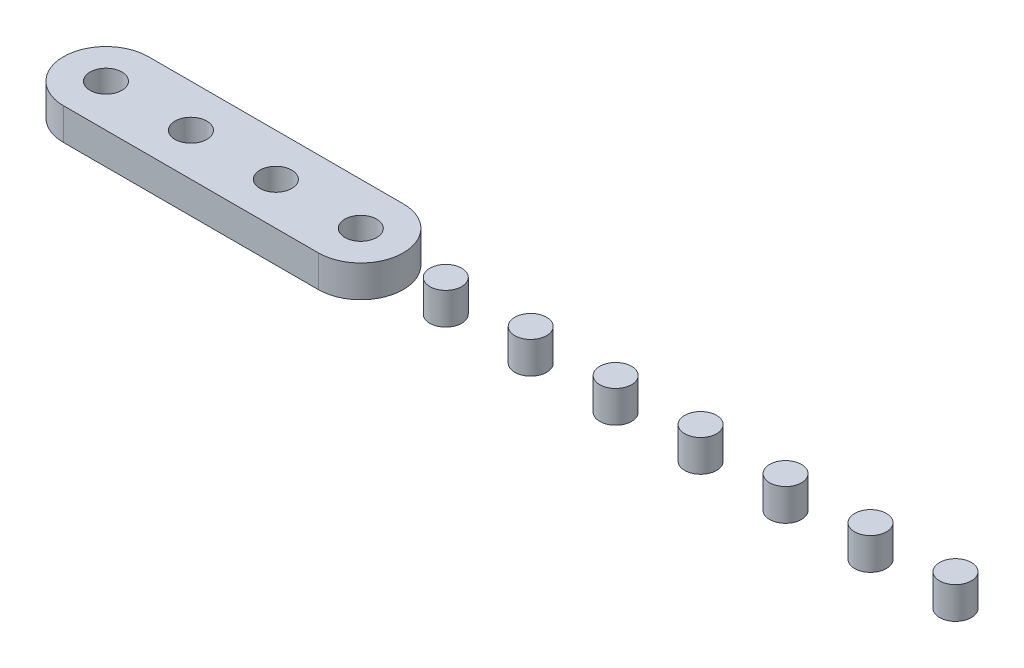
SolidWorks part; units mm, degrees
ref_plane "Front Plane" through (0, 0, 0) normal (0, 0, 1) x (1, 0, 0)
ref_plane "Top Plane" through (0, 0, 0) normal (0, 1, 0) x (1, 0, 0)
ref_plane "Right Plane" through (0, 0, 0) normal (1, 0, 0) x (0, 0, -1)
sketch "Sketch2" plane through (0, 0, 0) normal (0, 1, 0) x (1, 0, 0)
  line L0 (0, 0) -> (24, 0) construction
  line L1 (0, 4) -> (24, 4)
  line L2 (0, -4) -> (24, -4)
  arc A0 (0, 4) -> (0, -4) centre (0, 0) ccw
  arc A1 (24, -4) -> (24, 4) centre (24, 0) ccw
  circle A2 centre (0, 0) radius 1.5
  circle A3 centre (8, 0) radius 1.5
  circle A4 centre (16, 0) radius 1.5
  circle A5 centre (24, 0) radius 1.5
  circle A6 centre (32, 0) radius 1.5
  circle A7 centre (40, 0) radius 1.5
  circle A8 centre (48, 0) radius 1.5
  circle A9 centre (56, 0) radius 1.5
  circle A10 centre (64, 0) radius 1.5
  circle A11 centre (72, 0) radius 1.5
  circle A12 centre (80, 0) radius 1.5
  point P3 (12, 0)
  dimension "D1" = 3
  dimension "D2" = 8
  dimension "D3" = 24
extrude "Boss-Extrude2" add sketch "Sketch2" along normal blind 3
